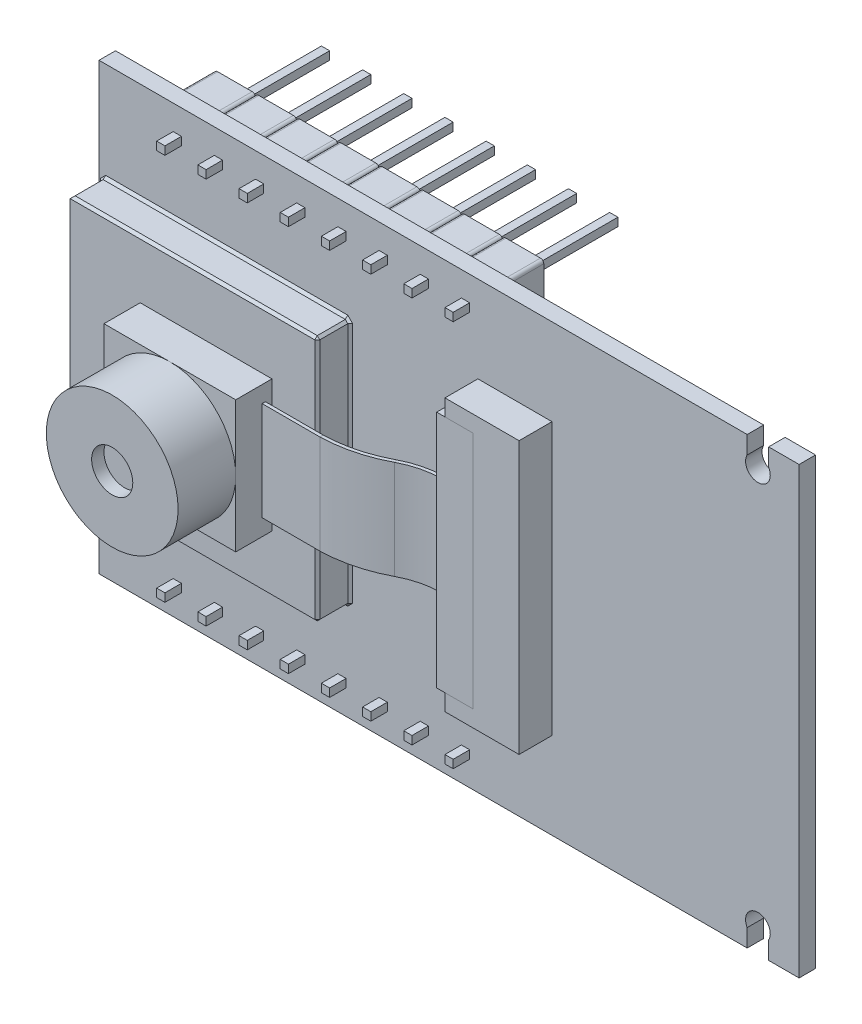
SolidWorks part; units mm, degrees
ref_plane "Front Plane" through (0, 0, 0) normal (0, 0, 1) x (1, 0, 0)
ref_plane "Top Plane" through (0, 0, 0) normal (0, 1, 0) x (1, 0, 0)
ref_plane "Right Plane" through (0, 0, 0) normal (1, 0, 0) x (0, 0, -1)
sketch "Sketch1" plane through (0, 0, 0) normal (0, 0, 1) x (1, 0, 0)
  line L0 (18.75, -13.5) -> (18.75, 13.5) construction
  line L1 (-21.25, -13.5) -> (18.1, -13.5)
  line L2 (-21.25, -13.5) -> (-21.25, 13.5)
  line L3 (-21.25, 13.5) -> (18.1, 13.5)
  line L4 (21.25, -13.5) -> (21.25, 13.5)
  line L5 (18.1, 12.4242) -> (18.1, 13.5)
  line L6 (19.4, 12.4242) -> (19.4, 13.5)
  line L7 (19.4, 13.5) -> (21.25, 13.5)
  line L8 (-1000, 0) -> (49000, 0) construction
  line L9 (19.4, -12.4242) -> (19.4, -13.5)
  line L10 (18.1, -12.4242) -> (18.1, -13.5)
  line L11 (19.4, -13.5) -> (21.25, -13.5)
  arc A0 (18.1, 12.4242) -> (19.4, 12.4242) centre (18.75, 12.05) ccw
  arc A1 (18.1, -12.4242) -> (19.4, -12.4242) centre (18.75, -12.05) cw
  dimension "D6" = 1.5
  dimension "D7" = 2.2
  dimension "D1" = 42.5
  dimension "D2" = 27
  dimension "D4" = 21.25
  dimension "D5" = 2.5
  dimension "D8" = 1.3
  dimension "D9" = 0.65
extrude "Boss-Extrude1" add sketch "Sketch1" along normal blind 1
sketch "Sketch2" plane through (0, 0, 1) normal (0, 0, 1) x (1, 0, 0)
  line L1 (-21, -7.5) -> (-6, -7.5)
  line L2 (-21, -7.5) -> (-21, 7.5)
  line L3 (-21, 7.5) -> (-6, 7.5)
  line L4 (-6, -7.5) -> (-6, 7.5)
  line L5 (-21.25, -13.5) -> (18.1, -13.5) construction
  line L6 (-21.25, 13.5) -> (-21.25, -13.5) construction
  point P8 (0, 0)
  point P9 (0, 0)
  dimension "D1" = 15
  dimension "D2" = 15
  dimension "D3" = 6
  dimension "D4" = 0.25
extrude "Boss-Extrude2" add sketch "Sketch2" along normal blind 2
sketch "Sketch3" plane through (-21, 0, 0) normal (-1, 0, 0) x (0, 0, 1)
  line L1 (2.8, 6.4) -> (2.05, 6.4)
  line L2 (2.8, 6.4) -> (2.8, -5.1)
  line L3 (2.8, -5.1) -> (2.05, -5.1)
  line L4 (2.05, 6.4) -> (2.05, -5.1)
  line L6 (3, 7.5) -> (3, -7.5) construction
  line L7 (3, 7.5) -> (1, 7.5) construction
  dimension "D1" = 11.5
  dimension "D2" = 0.75
  dimension "D3" = 1.1
  dimension "D4" = 0.2
extrude "Cut-Extrude1" cut sketch "Sketch3" against normal blind 7.5
sketch "Sketch4" plane through (0, 0, 0) normal (0, 0, -1) x (-1, 0, 0)
  line L0 (-21.25, -13.5) -> (-21.25, 13.5) construction
  line L1 (-11.25, -7.75) -> (5.75, -7.75)
  line L2 (-11.25, -7.75) -> (-11.25, 7.75)
  line L3 (-11.25, 7.75) -> (5.75, 7.75)
  line L4 (5.75, -7.75) -> (5.75, 7.75)
  line L6 (-11.25, 7.75) -> (-8.5, 7.75)
  line L7 (-11.25, 7.75) -> (-11.25, 2.25)
  line L8 (-11.25, 2.25) -> (-8.5, 2.25)
  line L9 (-8.5, 7.75) -> (-8.5, 2.25)
  dimension "D1" = 17
  dimension "D2" = 15.5
  dimension "D3" = 7.75
  dimension "D4" = 10
  dimension "D5" = 5.5
  dimension "D6" = 2.75
extrude "Boss-Extrude3" add sketch "Sketch4" along normal blind 3 contours L3 L9 L8 L2 L1 L4
chamfer "Chamfer2" distance 0.15 angle 45 11 edges at (-21, 0, 1) (-21, -7.5, 2) (-13.5, -7.5, 3) (-13.5, -7.5, 1) (-6, -7.5, 2) (-6, 0, 3) (-6, 0, 1) (-6, 7.5, 2) (-13.5, 7.5, 3) (-21, 7.5, 2) (-13.5, 7.5, 1)
sketch "Sketch6" plane through (0, 0, 0) normal (0, 0, -1) x (-1, 0, 0)
  line L0 (-21.25, -13.5) -> (-21.25, 13.5) construction
  line L1 (-18.75, -9) -> (6.25, -9)
  line L2 (-18.75, -9) -> (-18.75, 9)
  line L3 (-18.75, 9) -> (6.25, 9)
  line L4 (6.25, -9) -> (6.25, 9)
  line L5 (5.75, -7.75) -> (5.75, 7.75) construction
  dimension "D1" = 2.5
  dimension "D2" = 18
  dimension "D3" = 9
  dimension "D4" = 0.5
extrude "Boss-Extrude4" add sketch "Sketch6" along normal blind 1
sketch "Sketch7" plane through (0, 0, -1) normal (0, 0, -1) x (-1, 0, 0)
  line L0 (-8.5, 7.75) -> (-11.25, 7.75) construction
  line L1 (-11.25, 2.25) -> (-11.25, 7.75) construction
  line L3 (-11.25, 7.75) -> (-8.95, 7.75)
  line L4 (-11.25, 7.75) -> (-11.25, 5.45)
  line L5 (-11.25, 5.45) -> (-8.95, 5.45)
  line L6 (-8.95, 7.75) -> (-8.95, 5.45)
  dimension "D1" = 2.3
  dimension "D2" = 2.3
extrude "Boss-Extrude5" add sketch "Sketch7" along normal blind 0.15
sketch "Sketch8" plane through (0, 0, -1.15) normal (0, 0, -1) x (-1, 0, 0)
  line L0 (-8.95, 5.45) -> (-8.95, 7.75) construction
  line L1 (-11.25, 5.45) -> (-8.95, 5.45) construction
  circle A0 centre (-10.1, 6.6) radius 0.95
  circle A1 centre (-10.1, 6.6) radius 0.9
  circle A2 centre (-10.1, 6.6) radius 0.175
  dimension "D3" = 1.9
  dimension "D4" = 1.8
  dimension "D5" = 0.35
  dimension "D1" = 1.15
  dimension "D2" = 1.15
extrude "Boss-Extrude6" add sketch "Sketch8" along normal blind 0.6 contours A0 A1 | A2
sketch "Sketch9" plane through (0, 0, 0) normal (0, 0, -1) x (-1, 0, 0)
  line L0 (21.25, -13.5) -> (-18.1, -13.5) construction
  line L1 (15.45, -13) -> (17.55, -13)
  line L3 (15.45, -10.5) -> (17.55, -10.5)
  line L4 (17.75, -12.8) -> (17.75, -10.7)
  line L5 (21.25, 13.5) -> (21.25, -13.5) construction
  line L7 (12.95, -13) -> (15.05, -13)
  line L9 (12.95, -10.5) -> (15.05, -10.5)
  line L11 (10.45, -13) -> (12.55, -13)
  line L13 (10.45, -10.5) -> (12.55, -10.5)
  line L15 (7.95, -13) -> (10.05, -13)
  line L17 (7.95, -10.5) -> (10.05, -10.5)
  line L19 (5.45, -13) -> (7.55, -13)
  line L21 (5.45, -10.5) -> (7.55, -10.5)
  line L23 (2.95, -13) -> (5.05, -13)
  line L25 (2.95, -10.5) -> (5.05, -10.5)
  line L27 (0.45, -13) -> (2.55, -13)
  line L29 (0.45, -10.5) -> (2.55, -10.5)
  line L30 (-2.25, -12.8) -> (-2.25, -10.7)
  line L31 (-2.05, -13) -> (0.05, -13)
  line L33 (-2.05, -10.5) -> (0.05, -10.5)
  line L34 (-1000, 0) -> (49000, 0) construction
  line L35 (-2.05, 10.5) -> (0.05, 10.5)
  line L37 (-2.05, 13) -> (0.05, 13)
  line L38 (-2.25, 12.8) -> (-2.25, 10.7)
  line L39 (0.45, 10.5) -> (2.55, 10.5)
  line L41 (0.45, 13) -> (2.55, 13)
  line L43 (2.95, 10.5) -> (5.05, 10.5)
  line L45 (2.95, 13) -> (5.05, 13)
  line L47 (5.45, 10.5) -> (7.55, 10.5)
  line L49 (5.45, 13) -> (7.55, 13)
  line L51 (7.95, 10.5) -> (10.05, 10.5)
  line L53 (7.95, 13) -> (10.05, 13)
  line L55 (10.45, 10.5) -> (12.55, 10.5)
  line L57 (10.45, 13) -> (12.55, 13)
  line L59 (12.95, 10.5) -> (15.05, 10.5)
  line L61 (12.95, 13) -> (15.05, 13)
  line L63 (17.75, 12.8) -> (17.75, 10.7)
  line L64 (15.45, 10.5) -> (17.55, 10.5)
  line L66 (15.45, 13) -> (17.55, 13)
  line L67 (15.25, -12.8) -> (15.25, -10.7) [skipped]
  line L68 (12.75, -12.8) -> (12.75, -10.7) [skipped]
  line L69 (10.25, -12.8) -> (10.25, -10.7) [skipped]
  line L70 (7.75, -12.8) -> (7.75, -10.7) [skipped]
  line L71 (5.25, -12.8) -> (5.25, -10.7) [skipped]
  line L72 (2.75, -12.8) -> (2.75, -10.7) [skipped]
  line L73 (0.25, -12.8) -> (0.25, -10.7) [skipped]
  arc A0 (17.55, -10.5) -> (17.75, -10.7) centre (17.55, -10.7) cw
  arc A1 (15.25, -10.7) -> (15.45, -10.5) centre (15.45, -10.7) cw
  arc A2 (15.45, -13) -> (15.25, -12.8) centre (15.45, -12.8) cw
  arc A3 (17.55, -13) -> (17.75, -12.8) centre (17.55, -12.8) ccw
  arc A4 (12.95, -13) -> (12.75, -12.8) centre (12.95, -12.8) cw
  arc A5 (12.75, -10.7) -> (12.95, -10.5) centre (12.95, -10.7) cw
  arc A6 (15.05, -13) -> (15.25, -12.8) centre (15.05, -12.8) ccw
  arc A7 (15.05, -10.5) -> (15.25, -10.7) centre (15.05, -10.7) cw
  arc A8 (10.45, -13) -> (10.25, -12.8) centre (10.45, -12.8) cw
  arc A9 (10.25, -10.7) -> (10.45, -10.5) centre (10.45, -10.7) cw
  arc A10 (12.55, -13) -> (12.75, -12.8) centre (12.55, -12.8) ccw
  arc A11 (12.55, -10.5) -> (12.75, -10.7) centre (12.55, -10.7) cw
  arc A12 (7.95, -13) -> (7.75, -12.8) centre (7.95, -12.8) cw
  arc A13 (7.75, -10.7) -> (7.95, -10.5) centre (7.95, -10.7) cw
  arc A14 (10.05, -13) -> (10.25, -12.8) centre (10.05, -12.8) ccw
  arc A15 (10.05, -10.5) -> (10.25, -10.7) centre (10.05, -10.7) cw
  arc A16 (5.45, -13) -> (5.25, -12.8) centre (5.45, -12.8) cw
  arc A17 (5.25, -10.7) -> (5.45, -10.5) centre (5.45, -10.7) cw
  arc A18 (7.55, -13) -> (7.75, -12.8) centre (7.55, -12.8) ccw
  arc A19 (7.55, -10.5) -> (7.75, -10.7) centre (7.55, -10.7) cw
  arc A20 (2.95, -13) -> (2.75, -12.8) centre (2.95, -12.8) cw
  arc A21 (2.75, -10.7) -> (2.95, -10.5) centre (2.95, -10.7) cw
  arc A22 (5.05, -13) -> (5.25, -12.8) centre (5.05, -12.8) ccw
  arc A23 (5.05, -10.5) -> (5.25, -10.7) centre (5.05, -10.7) cw
  arc A24 (0.45, -13) -> (0.25, -12.8) centre (0.45, -12.8) cw
  arc A25 (0.25, -10.7) -> (0.45, -10.5) centre (0.45, -10.7) cw
  arc A26 (2.55, -13) -> (2.75, -12.8) centre (2.55, -12.8) ccw
  arc A27 (2.55, -10.5) -> (2.75, -10.7) centre (2.55, -10.7) cw
  arc A28 (-2.05, -13) -> (-2.25, -12.8) centre (-2.05, -12.8) cw
  arc A29 (-2.25, -10.7) -> (-2.05, -10.5) centre (-2.05, -10.7) cw
  arc A30 (0.05, -13) -> (0.25, -12.8) centre (0.05, -12.8) ccw
  arc A31 (0.05, -10.5) -> (0.25, -10.7) centre (0.05, -10.7) cw
  arc A32 (0.05, 10.5) -> (0.25, 10.7) centre (0.05, 10.7) ccw
  arc A33 (0.05, 13) -> (0.25, 12.8) centre (0.05, 12.8) cw
  arc A34 (-2.25, 10.7) -> (-2.05, 10.5) centre (-2.05, 10.7) ccw
  arc A35 (-2.05, 13) -> (-2.25, 12.8) centre (-2.05, 12.8) ccw
  arc A36 (2.55, 10.5) -> (2.75, 10.7) centre (2.55, 10.7) ccw
  arc A37 (2.55, 13) -> (2.75, 12.8) centre (2.55, 12.8) cw
  arc A38 (0.25, 10.7) -> (0.45, 10.5) centre (0.45, 10.7) ccw
  arc A39 (0.45, 13) -> (0.25, 12.8) centre (0.45, 12.8) ccw
  arc A40 (5.05, 10.5) -> (5.25, 10.7) centre (5.05, 10.7) ccw
  arc A41 (5.05, 13) -> (5.25, 12.8) centre (5.05, 12.8) cw
  arc A42 (2.75, 10.7) -> (2.95, 10.5) centre (2.95, 10.7) ccw
  arc A43 (2.95, 13) -> (2.75, 12.8) centre (2.95, 12.8) ccw
  arc A44 (7.55, 10.5) -> (7.75, 10.7) centre (7.55, 10.7) ccw
  arc A45 (7.55, 13) -> (7.75, 12.8) centre (7.55, 12.8) cw
  arc A46 (5.25, 10.7) -> (5.45, 10.5) centre (5.45, 10.7) ccw
  arc A47 (5.45, 13) -> (5.25, 12.8) centre (5.45, 12.8) ccw
  arc A48 (10.05, 10.5) -> (10.25, 10.7) centre (10.05, 10.7) ccw
  arc A49 (10.05, 13) -> (10.25, 12.8) centre (10.05, 12.8) cw
  arc A50 (7.75, 10.7) -> (7.95, 10.5) centre (7.95, 10.7) ccw
  arc A51 (7.95, 13) -> (7.75, 12.8) centre (7.95, 12.8) ccw
  arc A52 (12.55, 10.5) -> (12.75, 10.7) centre (12.55, 10.7) ccw
  arc A53 (12.55, 13) -> (12.75, 12.8) centre (12.55, 12.8) cw
  arc A54 (10.25, 10.7) -> (10.45, 10.5) centre (10.45, 10.7) ccw
  arc A55 (10.45, 13) -> (10.25, 12.8) centre (10.45, 12.8) ccw
  arc A56 (15.05, 10.5) -> (15.25, 10.7) centre (15.05, 10.7) ccw
  arc A57 (15.05, 13) -> (15.25, 12.8) centre (15.05, 12.8) cw
  arc A58 (12.75, 10.7) -> (12.95, 10.5) centre (12.95, 10.7) ccw
  arc A59 (12.95, 13) -> (12.75, 12.8) centre (12.95, 12.8) ccw
  arc A60 (17.55, 13) -> (17.75, 12.8) centre (17.55, 12.8) cw
  arc A61 (15.45, 13) -> (15.25, 12.8) centre (15.45, 12.8) ccw
  arc A62 (15.25, 10.7) -> (15.45, 10.5) centre (15.45, 10.7) ccw
  arc A63 (17.55, 10.5) -> (17.75, 10.7) centre (17.55, 10.7) ccw
  point P8 (15.25, -10.5)
  point P11 (15.25, -13)
  point P14 (17.75, -13)
  point P188 (17.75, 13)
  point P189 (15.25, 13)
  point P190 (15.25, 10.5)
  dimension "D3" = 0.2
  dimension "D1" = 2.5
  dimension "D2" = 2.5
  dimension "D4" = 0.5
  dimension "D5" = 3.5
  dimension "D6" = 8
extrude "Boss-Extrude7" add sketch "Sketch9" along normal blind 2.5
sketch "Sketch10" plane through (0, 0, -2.5) normal (0, 0, -1) x (-1, 0, 0)
  line L0 (-2.25, -10.7) -> (-2.25, -12.8) construction
  line L1 (-1.25, -12) -> (-0.75, -12)
  line L2 (-1.25, -12) -> (-1.25, -11.5)
  line L3 (-1.25, -11.5) -> (-0.75, -11.5)
  line L4 (-0.75, -12) -> (-0.75, -11.5)
  line L5 (-2.05, -13) -> (0.05, -13) construction
  line L6 (1.25, -12) -> (1.25, -11.5)
  line L7 (1.25, -12) -> (1.75, -12)
  line L8 (1.75, -12) -> (1.75, -11.5)
  line L9 (1.25, -11.5) -> (1.75, -11.5)
  line L10 (3.75, -12) -> (3.75, -11.5)
  line L11 (3.75, -12) -> (4.25, -12)
  line L12 (4.25, -12) -> (4.25, -11.5)
  line L13 (3.75, -11.5) -> (4.25, -11.5)
  line L14 (6.25, -12) -> (6.25, -11.5)
  line L15 (6.25, -12) -> (6.75, -12)
  line L16 (6.75, -12) -> (6.75, -11.5)
  line L17 (6.25, -11.5) -> (6.75, -11.5)
  line L18 (8.75, -12) -> (8.75, -11.5)
  line L19 (8.75, -12) -> (9.25, -12)
  line L20 (9.25, -12) -> (9.25, -11.5)
  line L21 (8.75, -11.5) -> (9.25, -11.5)
  line L22 (11.25, -12) -> (11.25, -11.5)
  line L23 (11.25, -12) -> (11.75, -12)
  line L24 (11.75, -12) -> (11.75, -11.5)
  line L25 (11.25, -11.5) -> (11.75, -11.5)
  line L26 (13.75, -12) -> (13.75, -11.5)
  line L27 (13.75, -12) -> (14.25, -12)
  line L28 (14.25, -12) -> (14.25, -11.5)
  line L29 (13.75, -11.5) -> (14.25, -11.5)
  line L30 (16.25, -12) -> (16.25, -11.5)
  line L31 (16.25, -12) -> (16.75, -12)
  line L32 (16.75, -12) -> (16.75, -11.5)
  line L33 (16.25, -11.5) -> (16.75, -11.5)
  line L34 (-1000, 0) -> (49000, 0) construction
  line L35 (16.25, 11.5) -> (16.75, 11.5)
  line L36 (16.75, 12) -> (16.75, 11.5)
  line L37 (16.25, 12) -> (16.75, 12)
  line L38 (16.25, 12) -> (16.25, 11.5)
  line L39 (13.75, 11.5) -> (14.25, 11.5)
  line L40 (14.25, 12) -> (14.25, 11.5)
  line L41 (13.75, 12) -> (14.25, 12)
  line L42 (13.75, 12) -> (13.75, 11.5)
  line L43 (11.25, 11.5) -> (11.75, 11.5)
  line L44 (11.75, 12) -> (11.75, 11.5)
  line L45 (11.25, 12) -> (11.75, 12)
  line L46 (11.25, 12) -> (11.25, 11.5)
  line L47 (8.75, 11.5) -> (9.25, 11.5)
  line L48 (9.25, 12) -> (9.25, 11.5)
  line L49 (8.75, 12) -> (9.25, 12)
  line L50 (8.75, 12) -> (8.75, 11.5)
  line L51 (6.25, 11.5) -> (6.75, 11.5)
  line L52 (6.75, 12) -> (6.75, 11.5)
  line L53 (6.25, 12) -> (6.75, 12)
  line L54 (6.25, 12) -> (6.25, 11.5)
  line L55 (3.75, 11.5) -> (4.25, 11.5)
  line L56 (4.25, 12) -> (4.25, 11.5)
  line L57 (3.75, 12) -> (4.25, 12)
  line L58 (3.75, 12) -> (3.75, 11.5)
  line L59 (1.25, 11.5) -> (1.75, 11.5)
  line L60 (1.75, 12) -> (1.75, 11.5)
  line L61 (1.25, 12) -> (1.75, 12)
  line L62 (1.25, 12) -> (1.25, 11.5)
  line L63 (-0.75, 12) -> (-0.75, 11.5)
  line L64 (-1.25, 11.5) -> (-0.75, 11.5)
  line L65 (-1.25, 12) -> (-1.25, 11.5)
  line L66 (-1.25, 12) -> (-0.75, 12)
  dimension "D1" = 0.5
  dimension "D2" = 0.5
  dimension "D3" = 1
  dimension "D4" = 1
  dimension "D5" = 8
extrude "Boss-Extrude8" add sketch "Sketch10" along normal blind 5.5 and the other way blind 4.5
sketch "Sketch11" plane through (0, 0, 1) normal (0, 0, 1) x (1, 0, 0)
  line L0 (21.25, -13.5) -> (21.25, 13.5) construction
  line L1 (1.75, -8.25) -> (6.25, -8.25)
  line L2 (1.75, -8.25) -> (1.75, 8.25)
  line L3 (1.75, 8.25) -> (6.25, 8.25)
  line L4 (6.25, -8.25) -> (6.25, 8.25)
  line L5 (1.25, -7.25) -> (3.45, -7.25)
  line L6 (1.25, -7.25) -> (1.25, 7.25)
  line L7 (1.25, 7.25) -> (3.45, 7.25)
  line L8 (3.45, -7.25) -> (3.45, 7.25)
  dimension "D1" = 16.5
  dimension "D2" = 4.5
  dimension "D3" = 2.2
  dimension "D4" = 0.5
  dimension "D5" = 14.5
  dimension "D6" = 7.25
  dimension "D7" = 8.25
  dimension "D8" = 15
extrude "Boss-Extrude9" add sketch "Sketch11" along normal blind 2 contours L8 L5 L2 L1 L4 L3 L7
sketch "Sketch12" plane through (0, 0, 3) normal (0, 0, 1) x (1, 0, 0)
  line L0 (1.75, -7.25) -> (1.25, -7.25) construction
  line L1 (3.45, 7.25) -> (1.25, 7.25)
  line L2 (3.45, 7.25) -> (3.45, -7.25)
  line L3 (3.45, -7.25) -> (1.25, -7.25)
  line L4 (1.25, 7.25) -> (1.25, -7.25)
  line L5 (6.25, -8.25) -> (6.25, 8.25) construction
  line L6 (1.75, 8.25) -> (6.25, 8.25) construction
  point P7 (0, 0)
  dimension "D1" = 2.2
  dimension "D2" = 2.8
  dimension "D3" = 1
split line "Split Line1"
sketch "Sketch13" plane through (0, 0, 3) normal (0, 0, 1) x (1, 0, 0)
  line L0 (-21.25, 13.5) -> (-21.25, -13.5) construction
  line L1 (-16.75, -4) -> (-8.75, -4)
  line L2 (-16.75, -4) -> (-16.75, 4)
  line L3 (-16.75, 4) -> (-8.75, 4)
  line L4 (-8.75, -4) -> (-8.75, 4)
  dimension "D1" = 8
  dimension "D2" = 8
  dimension "D3" = 4
  dimension "D4" = 4.5
extrude "Boss-Extrude12" add sketch "Sketch13" along normal blind 2.2
sketch "Sketch14" plane through (0, 0, 5.2) normal (0, 0, 1) x (1, 0, 0)
  line L0 (-8.75, -4) -> (-8.75, 4) construction
  circle A0 centre (-12.75, 0) radius 4
  circle A1 centre (-12.75, 0) radius 1.25
  dimension "D2" = 8
  dimension "D3" = 2.5
  dimension "D1" = 4
extrude "Boss-Extrude13" add sketch "Sketch14" along normal blind 3.5
sketch "Sketch15" plane through (0, 0, 5.2) normal (0, 0, 1) x (1, 0, 0)
  circle A1 centre (-12.75, 0) radius 1.25
  circle A2 centre (-12.75, 0) radius 1.25
  dimension "D1" = 0
extrude "Boss-Extrude14" add sketch "Sketch15" along normal blind 2.75
sketch "Sketch16" plane through (0, -13.5, 0) normal (0, -1, 0) x (1, 0, 0)
  line L0 (1.25, 2) -> (0.6495, 2)
  line L1 (1.25, 3) -> (1.25, 1) construction
  line L2 (-8.75, 3.5) -> (-5.2382, 3.5)
  line L3 (-8.75, 5.2) -> (-8.75, 3) construction
  line L4 (-21, 3) -> (-6.15, 3) construction
  arc A0 (-1.6836, 2.5777) -> (-5.2382, 3.5) centre (-5.4165, -4.498) ccw
  arc A1 (-1.6836, 2.5777) -> (0.6495, 2) centre (0.6495, 7) ccw
  point P13 (-0.75, 2)
  dimension "D3" = 8
  dimension "D5" = 5
  dimension "D1" = 0.5
  dimension "D2" = 2
  dimension "D4" = 5.4165
sketch "Sketch17" plane through (1.25, 0, 0) normal (-1, 0, 0) x (0, 0, 1)
  line L1 (1.9, -3) -> (2.1, -3)
  line L2 (1.9, -3) -> (1.9, 3)
  line L3 (1.9, 3) -> (2.1, 3)
  line L4 (2.1, -3) -> (2.1, 3)
  dimension "D1" = 6
  dimension "D2" = 3
  dimension "D3" = 0.2
  dimension "D4" = 0.1
sweep "Sweep1" add profiles "Sketch17" path "Sketch16"
